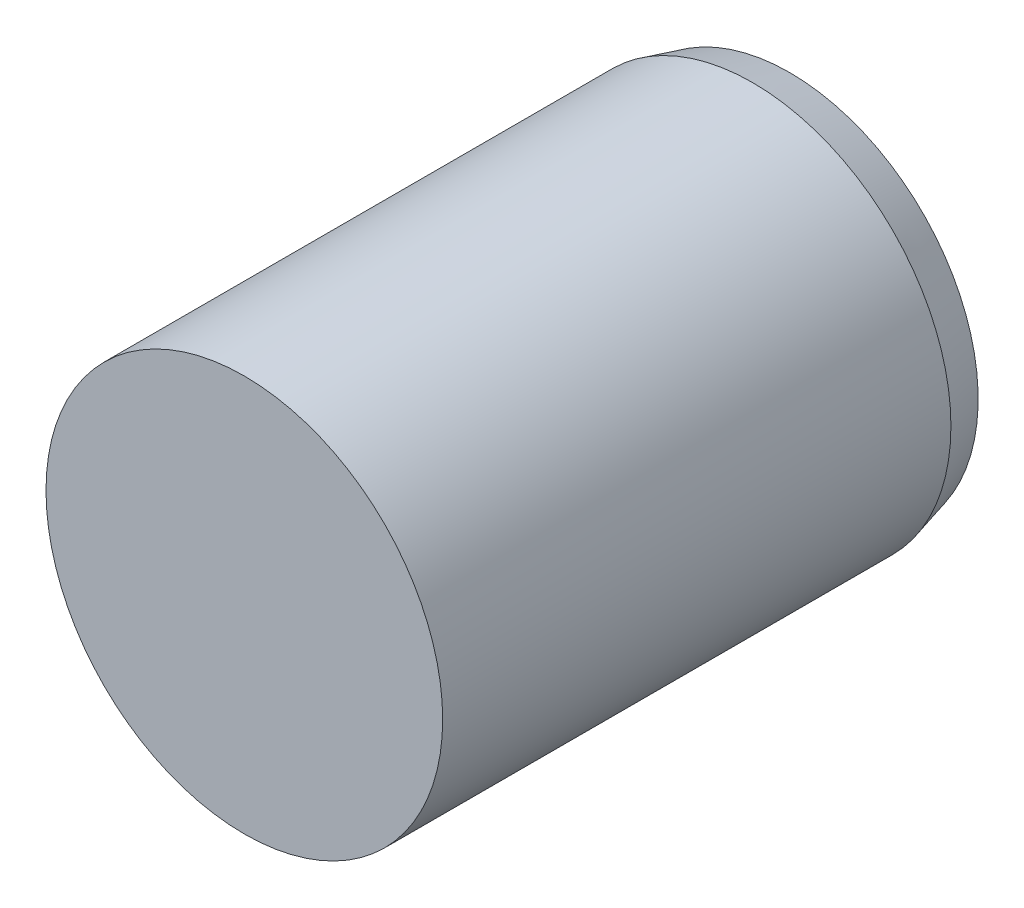
SolidWorks part; units mm, degrees
material "416 SS"
ref_plane "Front Plane" through (0, 0, 0) normal (0, 0, 1) x (1, 0, 0)
ref_plane "Top Plane" through (0, 0, 0) normal (0, 1, 0) x (1, 0, 0)
ref_plane "Right Plane" through (0, 0, 0) normal (1, 0, 0) x (0, 0, -1)
sketch "Sketch1" plane through (0, 0, 0) normal (1, 0, 0) x (0, 0, -1)
  line L0 (-6.35, 0) -> (6.35, 0) construction
  point P2 (0, 0)
  dimension "Length" = 12.7
sketch "Sketch2" plane through (0, 0, 0) normal (0, 0, 1) x (1, 0, 0)
  circle A0 centre (0, 0) radius 3.175
  point P3 (0, 3.175)
  dimension "Diameter" = 6.35
sketch "Sketch3" plane through (0, 0, 0) normal (1, 0, 0) x (0, 0, -1)
  line L0 (-6.35, 2.3812) -> (-5.5562, 3.175)
  line L1 (-6.35, 0) -> (6.35, 0)
  line L2 (-6.35, 0) -> (-6.35, 2.3812)
  line L3 (-5.5562, 3.175) -> (5.7547, 3.175)
  line L4 (6.35, 0) -> (6.35, 3.0155)
  line L5 (6.35, 3.0155) -> (5.7547, 3.175)
  dimension "D1" = 45
  dimension "D2" = 0.7937
  dimension "D3" = 15
  dimension "D4" = 0.5953
revolve "Revolve1" add sketch "Sketch3" angle 360 about L1
sketch "Sketch4" plane through (0, 0, 6.35) normal (0, 0, 1) x (1, 0, 0)
  circle A1 centre (0, 0) radius 3.175
  circle A2 centre (0, 0) radius 3.175
  dimension "D1" = 0
extrude "Cut-Extrude1" cut sketch "Sketch4" against normal blind 3.9688
equation "\"D2@Sketch3\"=0.125*\"Diameter@Sketch2\""
equation "\"D4@Sketch3\"=0.75*\"D2@Sketch3\""
